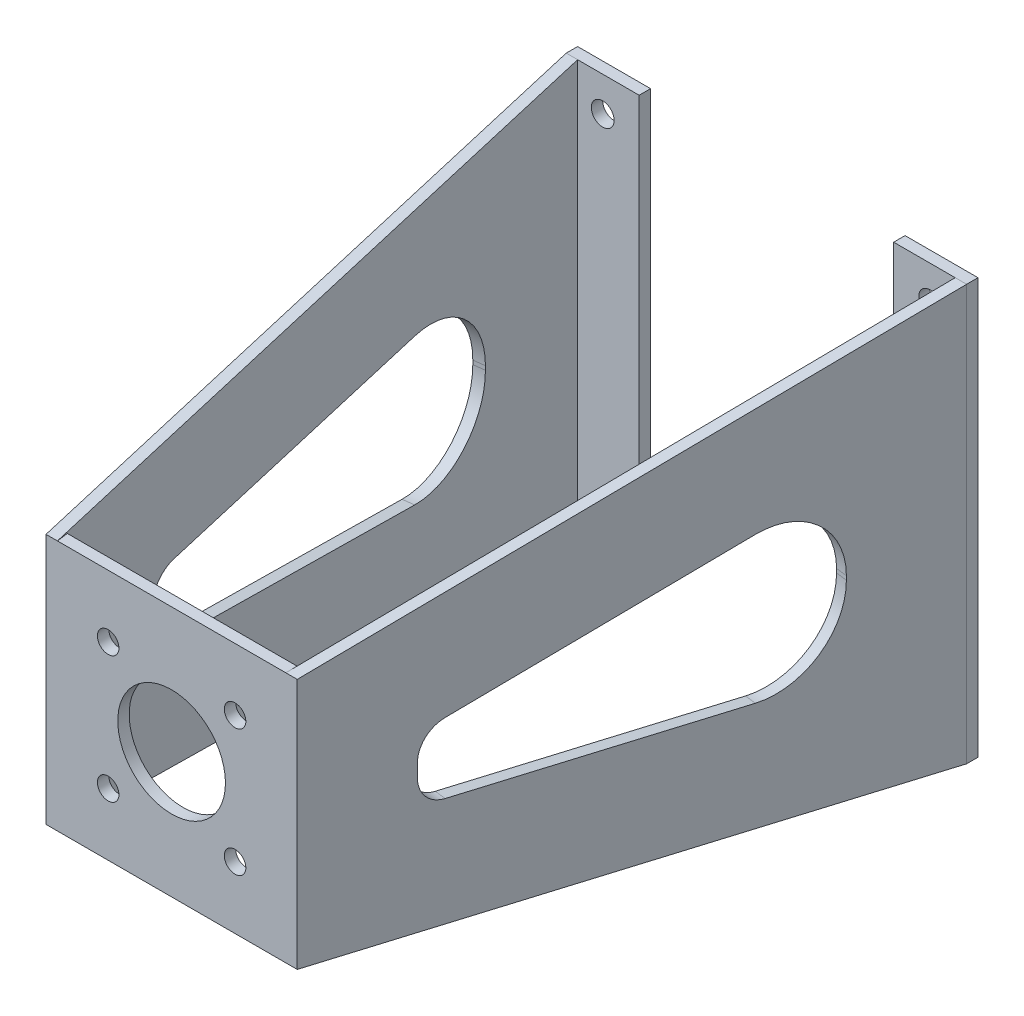
SolidWorks part; units mm, degrees
material "2014 Alloy"
ref_plane "Front Plane" through (0, 0, 0) normal (0, 0, 1) x (1, 0, 0)
ref_plane "Top Plane" through (0, 0, 0) normal (0, 1, 0) x (1, 0, 0)
ref_plane "Right Plane" through (0, 0, 0) normal (1, 0, 0) x (0, 0, -1)
sketch "Sketch1" plane through (0, 0, 0) normal (0, 0, 1) x (1, 0, 0)
  line L0 (-93.7, 28.9306) -> (-93.7, -28.9306)
  line L1 (-12.5, -12.5) -> (12.5, -12.5) construction
  line L2 (-12.5, -12.5) -> (-12.5, 12.5) construction
  line L3 (-12.5, 12.5) -> (12.5, 12.5) construction
  line L4 (12.5, -12.5) -> (12.5, 12.5) construction
  line L5 (-12.5, -12.5) -> (12.5, 12.5) construction
  line L6 (-12.5, 12.5) -> (12.5, -12.5) construction
  line L7 (-17.5, -17.5) -> (17.5, -17.5)
  line L8 (-17.5, -17.5) -> (-17.5, 17.5)
  line L9 (-17.5, 17.5) -> (17.5, 17.5)
  line L10 (17.5, -17.5) -> (17.5, 17.5)
  line L11 (-17.5, -17.5) -> (17.5, 17.5) construction
  line L12 (-17.5, 17.5) -> (17.5, -17.5) construction
  line L13 (-93.7, -28.9306) -> (-17.5, -17.5)
  line L14 (-17.5, 17.5) -> (-93.7, 28.9306)
  line L15 (-93.7, 0) -> (-17.5, 0) construction
  line L16 (-93.7, 28.9306) -> (-103.86, 28.9306)
  line L17 (-103.86, 28.9306) -> (-103.86, -28.9306)
  line L18 (-103.86, -28.9306) -> (-93.7, -28.9306)
  line L19 (-98.78, 24.13) -> (-98.78, -24.13) construction
  circle A0 centre (0, 0) radius 7.5
  circle A1 centre (0, 0) radius 12.5 construction
  circle A2 centre (8.8388, 8.8388) radius 1.5
  circle A3 centre (8.8388, -8.8388) radius 1.5
  circle A4 centre (-8.8388, -8.8388) radius 1.5
  circle A5 centre (-98.78, 24.13) radius 1.5875
  circle A6 centre (-98.78, -24.13) radius 1.5875
  circle A7 centre (-8.8388, 8.8388) radius 1.5
  point P0 (0, 0)
  point P29 (-98.78, 0)
  dimension "D2" = 15
  dimension "D4" = 3
  dimension "D8" = 3.175
  dimension "D3" = 25
  dimension "D5" = 35
  dimension "D6" = 35
  dimension "D7" = 48.26
  dimension "D9" = 57.8612
  dimension "D10" = 76.2
  dimension "D11" = 10.16
  dimension "D12" = 5.08
extrude "Boss-Extrude2" add sketch "Sketch1" along normal blind 1.5875
ref_plane "Plane1" through (0, 0, -81.28) normal (0, 0, -1) x (-1, 0, 0)
sketch "Sketch15" plane through (0, 0, -81.28) normal (0, 0, -1) x (-1, 0, 0)
  line L0 (27.8892, 28.9306) -> (27.8892, -28.9306)
  line L1 (27.8892, 28.9306) -> (17.7292, 28.9306)
  line L2 (17.7292, 28.9306) -> (17.7292, -28.9306)
  line L3 (17.7292, -28.9306) -> (27.8892, -28.9306)
  line L4 (22.8092, 24.13) -> (22.8092, -24.13) construction
  line L5 (22.8092, 0) -> (0, 0) construction
  circle A0 centre (22.8092, 24.13) radius 1.5875
  circle A1 centre (22.8092, -24.13) radius 1.5875
  point P9 (22.8092, 0)
  dimension "D4" = 3.175
  dimension "D5" = 22.8092
  dimension "D1" = 10.16
  dimension "D2" = 57.8612
  dimension "D3" = 5.08
  dimension "D6" = 48.26
  dimension "D7" = 4.8006
extrude "Boss-Extrude3" add sketch "Sketch15" along normal blind 1.5875
sketch3d "3DSketch1"
  line L0 (-17.5, 17.5, 1.5875) -> (-27.8892, 28.9306, -81.28)
  line L1 (-27.8892, -28.9306, -81.28) -> (-17.5, -17.5, 1.5875)
  line L2 (-27.8892, 28.9306, -81.28) -> (-27.8892, -28.9306, -81.28)
  line L3 (-17.5, -17.5, 1.5875) -> (-17.5, 17.5, 1.5875)
  line L4 (-27.8892, 28.9306, -81.28) -> (0.4153, 46.2187, -82.4439) construction
extrude "Boss-Extrude4" add sketch "3DSketch1" along direction (1, 0, 0) on the side of the normal blind 1.5875
sketch "Sketch16" plane through (-17.4251, 0, 2.1846) normal (-0.9922, 0, 0.1244) x (0.1244, 0, 0.9922)
  line L12 (-15.6018, -4.4132) -> (-15.6018, 4.4132)
  line L13 (-15.6018, 4.4132) -> (-69.118, 11.7378)
  line L14 (-69.118, 11.7378) -> (-69.118, -11.7378)
  line L15 (-69.118, -11.7378) -> (-15.6018, -4.4132)
  line L16 (-15.6018, -0.9233) -> (-15.6018, 0.9233)
  line L17 (-19.0594, 4.8864) -> (-57.762, 10.1835)
  line L18 (-69.118, 0.2759) -> (-69.118, -0.2759)
  line L19 (-57.762, -10.1835) -> (-19.0594, -4.8864)
  arc A0 (-69.118, -0.2759) -> (-57.762, -10.1835) centre (-59.118, -0.2759) ccw
  arc A1 (-69.118, 0.2759) -> (-57.762, 10.1835) centre (-59.118, 0.2759) cw
  arc A2 (-15.6018, -0.9233) -> (-19.0594, -4.8864) centre (-19.6018, -0.9233) cw
  arc A3 (-15.6018, 0.9233) -> (-19.0594, 4.8864) centre (-19.6018, 0.9233) ccw
  dimension "D2" = 10
  dimension "D3" = 4
  dimension "D1" = 15
extrude "Cut-Extrude1" cut sketch "Sketch16" against normal blind 1.5875
ref_plane "Plane2" through (0, 0, 0) normal (1, 0, 0) x (0, 0, -1)
mirror "Mirror8" about plane through (0, 0, 0) normal (1, 0, 0) of "Boss-Extrude3", "Cut-Extrude1", "Boss-Extrude4"
sketch "Sketch18" plane through (0, 0, -81.28) normal (0, 0, -1) x (-1, 0, 0)
  line L0 (-17.7292, 28.9306) -> (-17.7292, -28.9306)
  line L1 (-17.7292, 28.9306) -> (-27.8892, 28.9306)
  line L2 (-27.8892, 28.9306) -> (-27.8892, -28.9306)
  line L3 (-27.8892, -28.9306) -> (-17.7292, -28.9306)
  line L4 (-22.8092, 24.13) -> (-22.8092, -24.13) construction
  line L5 (-22.8092, 0) -> (-48.5137, 0) construction
  line L7 (-27.8892, 28.9306) -> (-26.3017, 28.9306) construction
  line L8 (-27.8892, 28.9306) -> (-27.8892, -28.9306) construction
  circle A0 centre (-22.8092, 24.13) radius 1.5875
  circle A1 centre (-22.8092, -24.13) radius 1.5875
  point P9 (-22.8092, 0)
  dimension "D4" = 3.175
  dimension "D1" = 10.16
  dimension "D2" = 57.8612
  dimension "D3" = 5.08
  dimension "D5" = 48.26
  dimension "D6" = 4.8006
extrude "Boss-Extrude5" add sketch "Sketch18" along normal blind 1.5875
